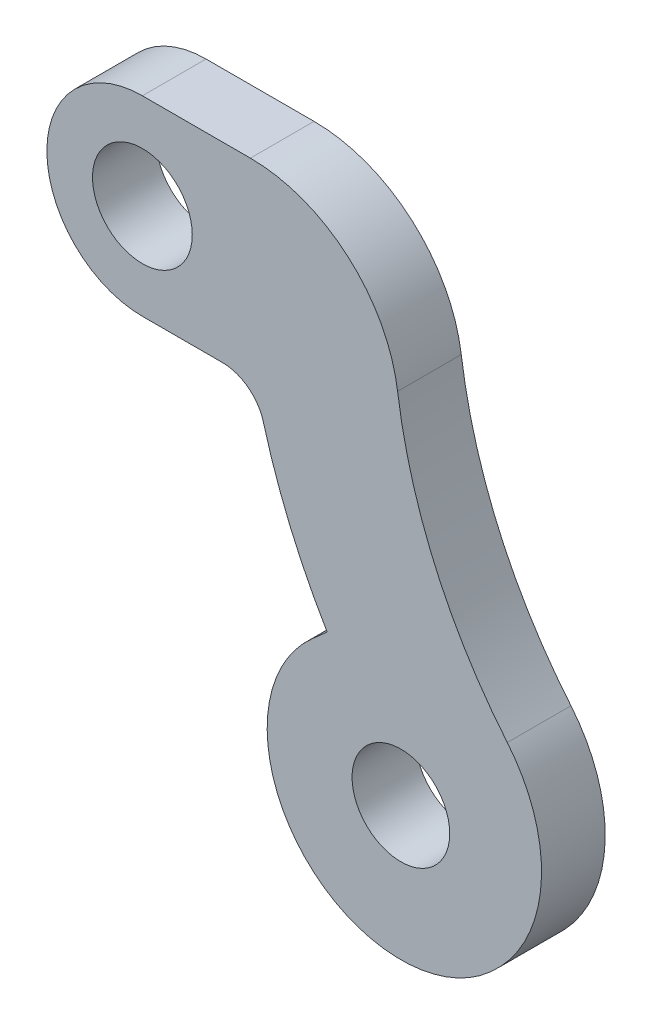
SolidWorks part; units mm, degrees
ref_plane "Front Plane" through (0, 0, 0) normal (0, 0, 1) x (1, 0, 0)
ref_plane "Top Plane" through (0, 0, 0) normal (0, 1, 0) x (1, 0, 0)
ref_plane "Right Plane" through (0, 0, 0) normal (1, 0, 0) x (0, 0, -1)
sketch "Sketch1" plane through (0, 0, -130.2439) normal (0, 0, 1) x (1, 0, 0)
  line L0 (-15.7081, 37.5725) -> (-15.0101, 38.1894) construction
  line L6 (-15.7081, 37.5725) -> (-15.0101, 38.1894)
  line L21 (1.2909, 35.7798) -> (-7.3644, 28.1309) construction
  line L22 (-17.5363, 52.8349) -> (-17.5363, 78.2517)
  line L23 (-1.1666, 35.6099) -> (-8.3577, 29.2549)
  line L26 (-14.7148, 36.4485) -> (-13.0642, 37.9072)
  line L31 (-7.2743, 28.2105) -> (-7.3644, 28.1309)
  line L35 (-23.7161, 46.719) -> (-19.9422, 46.719)
  line L36 (-23.7161, 55.719) -> (-18.6268, 55.719)
  arc A21 (-11.5363, 35.1017) -> (-11.5363, 30.6017) centre (-11.5363, 32.8517) ccw construction
  arc A22 (30.9499, 61.6319) -> (-1.1666, 35.6099) centre (11.4637, 52.8517) ccw
  arc A23 (-17.5363, 52.8349) -> (-13.0642, 37.9072) centre (9.6137, 52.8349) ccw
  arc A24 (-14.7148, 36.4485) -> (-8.3577, 29.2549) centre (-11.5363, 32.8517) ccw
  arc A25 (-9.8393, 51.1233) -> (-0.3376, 35.0322) centre (11.4637, 52.8517) ccw
  arc A28 (-11.5363, 30.6017) -> (-11.5363, 35.1017) centre (-11.5363, 32.8517) ccw construction
  arc A29 (-11.5363, 35.1017) -> (-11.5363, 30.6017) centre (-11.5363, 32.8517) ccw
  arc A30 (-11.5363, 30.6017) -> (-11.5363, 35.1017) centre (-11.5363, 32.8517) ccw
  arc A31 (-15.7081, 37.5725) -> (-7.3644, 28.1309) centre (-11.5363, 32.8517) ccw construction
  arc A32 (-19.9422, 46.719) -> (-18.0136, 45.2485) centre (-19.9422, 44.719) cw
  arc A33 (-15.7081, 37.5725) -> (-7.3644, 28.1309) centre (-11.5363, 32.8517) ccw
  circle A35 centre (-23.7161, 51.219) radius 2.25
  arc A36 (-23.7161, 55.719) -> (-23.7161, 46.719) centre (-23.7161, 51.219) ccw
  arc A40 (-11.6919, 49.6714) -> (-6.5229, 37.926) centre (11.4637, 52.8517) ccw
  arc A41 (-18.0136, 45.2485) -> (-15.0101, 38.1894) centre (9.6137, 52.8349) ccw
  arc A42 (-19.0363, 52.8517) -> (-15.0101, 38.1894) centre (9.6137, 52.8349) ccw construction
  arc A43 (-11.8327, 50.9616) -> (-1.4419, 33.3648) centre (11.4637, 52.8517) ccw construction
  arc A44 (-6.5229, 37.926) -> (-7.2743, 28.2105) centre (-11.9097, 33.4558) cw
  arc A45 (-11.6919, 49.6714) -> (-18.6268, 55.719) centre (-18.6268, 48.719) ccw
  circle A46 centre (-23.7161, 51.219) radius 2.35
  circle A47 centre (-11.5363, 32.8517) radius 2.3
  point P25 (-9.7161, 55.719)
  line M29 (-19.0363, 78.2517) -> (-19.0363, 52.8517)
  arc M30 (-19.0363, 52.8517) -> (-15.0101, 38.1894) centre (9.6137, 52.8349) ccw
  line M31 (-15.0101, 38.1894) -> (-15.7081, 37.5725)
  arc M32 (-15.7081, 37.5725) -> (-7.3644, 28.1309) centre (-11.5363, 32.8517) ccw
  line M33 (-7.3644, 28.1309) -> (1.2909, 35.7798)
  circle M35 centre (-11.5363, 32.8517) radius 2.25
  dimension "D1" = 1.5
  dimension "D2" = 2
  dimension "D3" = 7
  dimension "D4" = 2
  dimension "D5" = 4.5
  dimension "D6" = 14
  dimension "D7" = 4.7
  dimension "D8" = 4.6
extrude "Boss-Extrude2" add sketch "Sketch1" along normal blind 3 contours L36 A36 L35 A32 A35 M30 M29 | A40 A45 L36 A44 M29 M30 M31 M32 M33 M35
